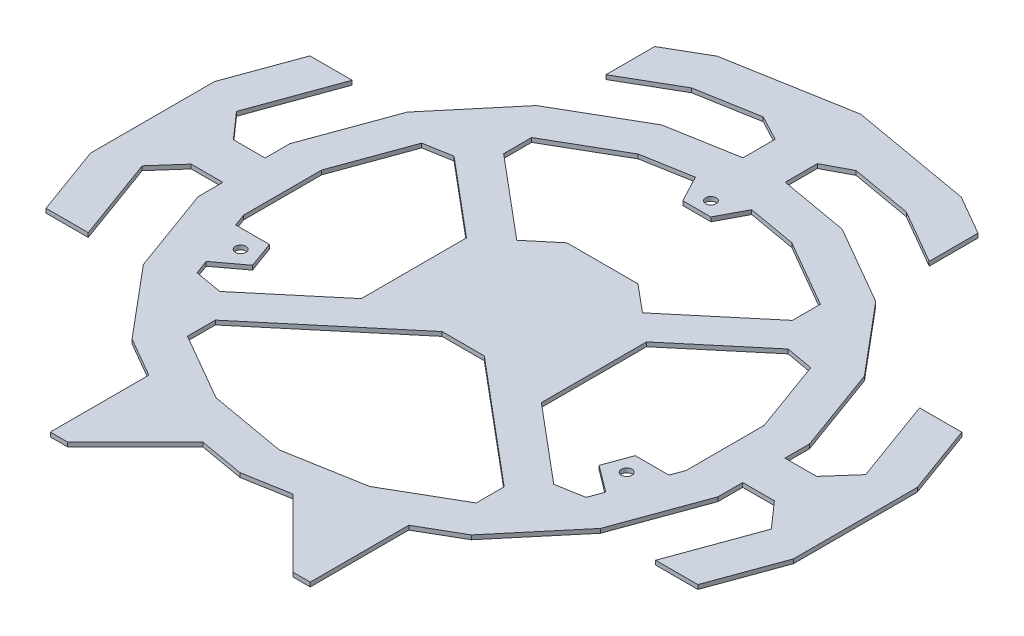
SolidWorks part; units mm, degrees
ref_plane "Front Plane" through (0, 0, 0) normal (0, 0, 1) x (1, 0, 0)
ref_plane "Top Plane" through (0, 0, 0) normal (0, 1, 0) x (1, 0, 0)
ref_plane "Right Plane" through (0, 0, 0) normal (1, 0, 0) x (0, 0, -1)
sketch "Sketch1" plane through (0, 0, 0) normal (0, 1, 0) x (1, 0, 0)
  line L1 (0, 75) -> (-25.6515, 70.4769)
  line L2 (-25.6515, 70.4769) -> (-48.2091, 57.4533)
  line L3 (-48.2091, 57.4533) -> (-64.9519, 37.5)
  line L4 (-64.9519, 37.5) -> (-73.8606, 13.0236)
  line L5 (-73.8606, 13.0236) -> (-73.8606, -13.0236)
  line L6 (-73.8606, -13.0236) -> (-64.9519, -37.5)
  line L7 (-64.9519, -37.5) -> (-48.2091, -57.4533)
  line L8 (-48.2091, -57.4533) -> (-25.6515, -70.4769)
  line L9 (-25.6515, -70.4769) -> (0, -75)
  line L10 (0, -75) -> (25.6515, -70.4769)
  line L11 (25.6515, -70.4769) -> (48.2091, -57.4533)
  line L12 (48.2091, -57.4533) -> (64.9519, -37.5)
  line L13 (64.9519, -37.5) -> (73.8606, -13.0236)
  line L14 (73.8606, -13.0236) -> (73.8606, 13.0236)
  line L15 (73.8606, 13.0236) -> (64.9519, 37.5)
  line L16 (64.9519, 37.5) -> (48.2091, 57.4533)
  line L17 (48.2091, 57.4533) -> (25.6515, 70.4769)
  line L18 (25.6515, 70.4769) -> (0, 75)
  line L19 (0, 63.8303) -> (-21.8313, 59.9809)
  line L20 (-21.8313, 59.9809) -> (-41.0293, 48.8969)
  line L21 (-41.0293, 48.8969) -> (-55.2787, 31.9152)
  line L22 (-55.2787, 31.9152) -> (-62.8606, 11.084)
  line L23 (-62.8606, 11.084) -> (-62.8606, -11.084)
  line L24 (-62.8606, -11.084) -> (-55.2787, -31.9152)
  line L25 (-55.2787, -31.9152) -> (-41.0293, -48.8969)
  line L26 (-41.0293, -48.8969) -> (-21.8313, -59.9809)
  line L27 (-21.8313, -59.9809) -> (0, -63.8303)
  line L28 (0, -63.8303) -> (21.8313, -59.9809)
  line L29 (21.8313, -59.9809) -> (41.0293, -48.8969)
  line L30 (41.0293, -48.8969) -> (55.2787, -31.9152)
  line L31 (55.2787, -31.9152) -> (62.8606, -11.084)
  line L32 (62.8606, -11.084) -> (62.8606, 11.084)
  line L33 (62.8606, 11.084) -> (55.2787, 31.9152)
  line L34 (55.2787, 31.9152) -> (41.0293, 48.8969)
  line L35 (41.0293, 48.8969) -> (21.8313, 59.9809)
  line L36 (21.8313, 59.9809) -> (0, 63.8303)
  circle A0 centre (0, 0) radius 73.8606 construction
  circle A1 centre (0, 0) radius 62.8606 construction
  point P1 (73.8606, 0)
  dimension "D1" = 150
  dimension "D2" = 11
extrude "Boss-Extrude1" add sketch "Sketch1" along normal blind 1.2
sketch "Sketch3" [suppressed] plane through (0, 1.6, 0) normal (0, 1, 0) x (1, 0, 0)
  line L0 (-73.8606, 13.0236) -> (-73.8606, -13.0236) construction
  line L1 (0, 62.8149) -> (-21.484, 59.0267)
  line L2 (-21.484, 59.0267) -> (-40.3766, 48.119)
  line L3 (-40.3766, 48.119) -> (-54.3993, 31.4074)
  line L4 (-54.3993, 31.4074) -> (-61.8606, 10.9077)
  line L5 (-61.8606, 10.9077) -> (-61.8606, -10.9077)
  line L6 (-61.8606, -10.9077) -> (-54.3993, -31.4074)
  line L7 (-54.3993, -31.4074) -> (-40.3766, -48.119)
  line L8 (-40.3766, -48.119) -> (-21.484, -59.0267)
  line L9 (-21.484, -59.0267) -> (0, -62.8149)
  line L10 (0, -62.8149) -> (21.484, -59.0267)
  line L11 (21.484, -59.0267) -> (40.3766, -48.119)
  line L12 (40.3766, -48.119) -> (54.3993, -31.4074)
  line L13 (54.3993, -31.4074) -> (61.8606, -10.9077)
  line L14 (61.8606, -10.9077) -> (61.8606, 10.9077)
  line L15 (61.8606, 10.9077) -> (54.3993, 31.4074)
  line L16 (54.3993, 31.4074) -> (40.3766, 48.119)
  line L17 (40.3766, 48.119) -> (21.484, 59.0267)
  line L18 (21.484, 59.0267) -> (0, 62.8149)
  line L19 (0, -98.3548) -> (33.6393, -92.4233)
  line L20 (33.6393, -92.4233) -> (63.2213, -75.3442)
  line L21 (63.2213, -75.3442) -> (85.1778, -49.1774)
  line L22 (85.1778, -49.1774) -> (96.8606, -17.0791)
  line L23 (96.8606, -17.0791) -> (96.8606, 17.0791)
  line L24 (96.8606, 17.0791) -> (85.1778, 49.1774)
  line L25 (85.1778, 49.1774) -> (63.2213, 75.3442)
  line L26 (63.2213, 75.3442) -> (33.6393, 92.4233)
  line L27 (33.6393, 92.4233) -> (0, 98.3548)
  line L28 (0, 98.3548) -> (-33.6393, 92.4233)
  line L29 (-33.6393, 92.4233) -> (-63.2213, 75.3442)
  line L30 (-63.2213, 75.3442) -> (-85.1778, 49.1774)
  line L31 (-85.1778, 49.1774) -> (-96.8606, 17.0791)
  line L32 (-96.8606, 17.0791) -> (-96.8606, -17.0791)
  line L33 (-96.8606, -17.0791) -> (-85.1778, -49.1774)
  line L34 (-85.1778, -49.1774) -> (-63.2213, -75.3442)
  line L35 (-63.2213, -75.3442) -> (-33.6393, -92.4233)
  line L36 (-33.6393, -92.4233) -> (0, -98.3548)
  circle A0 centre (0, 0) radius 61.8606 construction
  circle A1 centre (0, 0) radius 96.8606 construction
  dimension "D1" = 23
  dimension "D2" = 21.8154
sketch "Sketch15" plane through (0, 0, 0) normal (0, -1, 0) x (1, 0, 0)
  line L1 (0, -101.4011) -> (34.6812, -95.2859)
  line L2 (34.6812, -95.2859) -> (36.9303, -93.9874)
  line L4 (92.6205, -37.5) -> (99.8606, -17.6081)
  line L5 (99.8606, -17.6081) -> (99.8606, 17.6081)
  line L6 (99.8606, 17.6081) -> (92.6205, 37.5)
  line L13 (-92.6205, 37.5) -> (-99.8606, 17.6081)
  line L14 (-99.8606, 17.6081) -> (-99.8606, -17.6081)
  line L15 (-99.8606, -17.6081) -> (-92.6205, -37.5)
  line L17 (-36.9303, -93.9874) -> (-34.6812, -95.2859)
  line L18 (-34.6812, -95.2859) -> (0, -101.4011)
  line L19 (-36.9303, -84.7497) -> (-36.9303, -93.9874)
  line L20 (0, -93.2777) -> (31.9028, -87.6523)
  line L21 (31.9028, -87.6523) -> (36.9303, -84.7497)
  line L23 (84.1071, -37.5) -> (91.8606, -16.1975)
  line L24 (91.8606, -16.1975) -> (91.8606, 16.1975)
  line L25 (91.8606, 16.1975) -> (84.1071, 37.5)
  line L32 (-84.1071, 37.5) -> (-91.8606, 16.1975)
  line L33 (-91.8606, 16.1975) -> (-91.8606, -16.1975)
  line L34 (-91.8606, -16.1975) -> (-84.1071, -37.5)
  line L36 (-36.9303, -84.7497) -> (-31.9028, -87.6523)
  line L37 (-31.9028, -87.6523) -> (0, -93.2777)
  line L38 (-73.8606, -13.0236) -> (-73.8606, 13.0236) construction
  line L39 (84.1071, -37.5) -> (92.6205, -37.5)
  line L40 (-84.1071, -37.5) -> (-92.6205, -37.5)
  line L41 (-84.1071, 37.5) -> (-92.6205, 37.5)
  line L42 (84.1071, 37.5) -> (92.6205, 37.5)
  line L43 (36.9303, -84.7497) -> (36.9303, -93.9874)
  line L46 (76.4976, -64.1891) -> (87.8159, -50.7005) [skipped]
  line L47 (70.3693, -59.0468) -> (80.7808, -46.6388) [skipped]
  line L48 (70.3693, 59.0468) -> (59.9577, 71.4548) [skipped]
  line L49 (87.8159, 50.7005) -> (65.1794, 77.6777) [skipped]
  line L50 (-65.1794, 77.6777) -> (-76.4976, 64.1891) [skipped]
  line L51 (-59.9577, 71.4548) -> (-70.3693, 59.0468) [skipped]
  line L52 (-76.4976, -64.1891) -> (-65.1794, -77.6777) [skipped]
  line L53 (-70.3693, -59.0468) -> (-59.9577, -71.4548) [skipped]
  line L54 (-34.6812, 95.2859) -> (-49.9303, 86.4818) [skipped]
  line L55 (-31.9028, 87.6523) -> (-45.9303, 79.5536) [skipped]
  line L56 (0, 101.4011) -> (-17.3406, 98.3435) [skipped]
  line L57 (0, 93.2777) -> (-15.9514, 90.465) [skipped]
  line L58 (31.9028, 87.6523) -> (0, 93.2777) [skipped]
  line L59 (34.6812, 95.2859) -> (0, 101.4011) [skipped]
  line L60 (49.9303, 86.4818) -> (34.6812, 95.2859) [skipped]
  line L61 (45.9303, 79.5536) -> (31.9028, 87.6523) [skipped]
  arc A0 (92.5521, -37.5) -> (92.5521, 37.5) centre (0, 0) ccw construction
  arc A1 (83.8577, -37.5) -> (83.8577, 37.5) centre (0, 0) ccw construction
  arc A4 (-83.8577, 37.5) -> (-83.8577, -37.5) centre (0, 0) ccw construction
  arc A5 (-92.5521, 37.5) -> (-92.5521, -37.5) centre (0, 0) ccw construction
  arc A6 (-36.9303, -84.1102) -> (36.9303, -84.1102) centre (0, 0) ccw construction
  arc A7 (-36.9303, -92.7809) -> (36.9303, -92.7809) centre (0, 0) ccw construction
  dimension "D4" = 157.7183
  dimension "D1" = 99.8606
  dimension "D3" = 36.9303
  dimension "D2" = 8
extrude "Boss-Extrude17" add sketch "Sketch15" against normal up to surface (1.2 mm away) separate body up to face at (0, 1.2, 0)
sketch "Sketch18" plane through (0, 0, 0) normal (0, -1, 0) x (1, 0, 0)
  line L0 (-91.8606, 6) -> (-73.8606, 6)
  line L1 (-91.8606, -16.1975) -> (-91.8606, 16.1975) construction
  line L2 (-73.8606, -13.0236) -> (-73.8606, 13.0236) construction
  line L3 (-91.8606, -6) -> (-73.8606, -6)
  line L4 (73.8606, 6) -> (91.8606, 6)
  line L5 (73.8606, 13.0236) -> (73.8606, -13.0236) construction
  line L6 (91.8606, 16.1975) -> (91.8606, -16.1975) construction
  line L7 (73.8606, -6) -> (91.8606, -6)
  line L8 (-91.8606, 6) -> (-91.8606, -6)
  line L9 (-73.8606, -6) -> (-73.8606, 6)
  line L10 (73.8606, 6) -> (73.8606, -6)
  line L11 (91.8606, -6) -> (91.8606, 6)
  line L12 (-6, -73.942) -> (-6, -92.2197)
  line L13 (0, -75) -> (-25.6515, -70.4769) construction
  line L14 (0, -93.2777) -> (-31.9028, -87.6523) construction
  line L15 (6, -73.942) -> (6, -92.2197)
  line L16 (25.6515, -70.4769) -> (0, -75) construction
  line L17 (31.9028, -87.6523) -> (0, -93.2777) construction
  line L18 (-6, -73.942) -> (0, -75)
  line L19 (0, -75) -> (6, -73.942)
  line L20 (6, -92.2197) -> (0, -93.2777)
  line L21 (0, -93.2777) -> (-6, -92.2197)
  point P8 (-91.8606, 0)
  dimension "D1" = 12
  dimension "D2" = 6
  dimension "D3" = 12
  dimension "D4" = 6
extrude "Boss-Extrude18" add sketch "Sketch18" against normal up to surface (1.2 mm away) up to face at (0, 1.2, 0)
sketch "Sketch19" plane through (0, 0, 0) normal (0, -1, 0) x (1, 0, 0)
  line L0 (-91.8606, 16.1975) -> (-82.8606, 6)
  line L2 (-73.8606, 6) -> (-91.8606, 6) construction
  line L3 (-91.8606, -16.1975) -> (-82.8606, -6)
  line L4 (-91.8606, -6) -> (-73.8606, -6) construction
  line L5 (-82.8606, -6) -> (-91.8606, -6)
  line L6 (-91.8606, -6) -> (-91.8606, -16.1975)
  line L7 (-82.8606, 6) -> (-91.8606, 6)
  line L8 (-91.8606, 6) -> (-91.8606, 16.1975)
  line L9 (91.8606, 16.1975) -> (82.8606, 6)
  line L10 (91.8606, 6) -> (73.8606, 6) construction
  line L11 (82.8606, 6) -> (91.8606, 6)
  line L12 (91.8606, 6) -> (91.8606, 16.1975)
  line L13 (91.8606, -16.1975) -> (82.8606, -6)
  line L14 (73.8606, -6) -> (91.8606, -6) construction
  line L15 (82.8606, -6) -> (91.8606, -6)
  line L16 (91.8606, -6) -> (91.8606, -16.1975)
  line L17 (18.9514, -89.936) -> (6, -83.0809)
  line L18 (31.9028, -87.6523) -> (6, -92.2197) construction
  line L19 (6, -92.2197) -> (6, -73.942) construction
  line L20 (6, -83.0809) -> (6, -92.2197)
  line L21 (6, -92.2197) -> (18.9514, -89.936)
  line L22 (-6, -83.0809) -> (-6, -92.2197)
  line L23 (-6, -73.942) -> (-6, -92.2197) construction
  line L24 (-6, -92.2197) -> (-18.9514, -89.936)
  line L25 (-6, -92.2197) -> (-31.9028, -87.6523) construction
  line L26 (-18.9514, -89.936) -> (-6, -83.0809)
extrude "Boss-Extrude19" add sketch "Sketch19" against normal up to surface (1.2 mm away) up to face at (0, 1.2, -20.0384)
sketch "Sketch20" plane through (0, 0, 0) normal (0, -1, 0) x (1, 0, 0)
  line L0 (-36.9303, 63.9651) -> (-36.9303, 91.9651)
  line L1 (-48.2091, 57.4533) -> (-25.6515, 70.4769) construction
  line L2 (-36.9303, 91.9651) -> (-32.0524, 91.9651)
  line L3 (-32.0524, 91.9651) -> (-12.8258, 72.7385)
  line L4 (-25.6515, 70.4769) -> (0, 75) construction
  line L6 (25.6515, 70.4769) -> (48.2091, 57.4533) construction
  line L7 (36.9303, 63.9651) -> (36.9303, 91.9651)
  line L8 (36.9303, 91.9651) -> (32.0524, 91.9651)
  line L9 (32.0524, 91.9651) -> (12.8258, 72.7385)
  line L10 (0, 75) -> (25.6515, 70.4769) construction
  line L11 (12.8258, 72.7385) -> (25.6515, 70.4769)
  line L12 (25.6515, 70.4769) -> (36.9303, 63.9651)
  line L13 (-12.8258, 72.7385) -> (-25.6515, 70.4769)
  line L14 (-25.6515, 70.4769) -> (-36.9303, 63.9651)
  dimension "D1" = 135
  dimension "D2" = 135
  dimension "D3" = 28
  dimension "D4" = 28
extrude "Boss-Extrude20" add sketch "Sketch20" against normal up to surface (1.2 mm away) up to face at (0, 1.2, -22.2084)
sketch "Sketch23" plane through (0, 1.2, 0) normal (0, 1, 0) x (1, 0, 0)
  line L0 (-92.6205, 37.5) -> (-80.6205, 37.5)
  line L1 (-80.6205, 37.5) -> (-89.392, 13.4005)
  line L2 (-91.8606, 16.1975) -> (-82.8606, 6) construction
  line L3 (-92.6205, -37.5) -> (-80.6205, -37.5)
  line L4 (-80.6205, -37.5) -> (-89.392, -13.4005)
  line L5 (-82.8606, -6) -> (-91.8606, -16.1975) construction
  line L8 (-99.8606, 17.6081) -> (-92.6205, 37.5) construction
  line L9 (-92.6205, -37.5) -> (-99.8606, -17.6081) construction
  line L10 (-92.6205, 37.5) -> (-99.8606, 17.6081)
  line L11 (-99.8606, 17.6081) -> (-99.8606, -17.6081)
  line L12 (-99.8606, -17.6081) -> (-92.6205, -37.5)
  line L13 (-89.392, -13.4005) -> (-89.392, 13.4005)
  line L14 (0, 63.8303) -> (0, -63.8303) construction
  line L15 (80.6205, -37.5) -> (89.392, -13.4005)
  line L16 (92.6205, -37.5) -> (80.6205, -37.5)
  line L17 (99.8606, -17.6081) -> (92.6205, -37.5)
  line L18 (99.8606, 17.6081) -> (99.8606, -17.6081)
  line L19 (92.6205, 37.5) -> (99.8606, 17.6081)
  line L20 (92.6205, 37.5) -> (80.6205, 37.5)
  line L21 (80.6205, 37.5) -> (89.392, 13.4005)
  line L22 (89.392, -13.4005) -> (89.392, 13.4005)
  dimension "D1" = 12
  dimension "D2" = 12
extrude "Boss-Extrude21" add sketch "Sketch23" against normal up to surface (1.2 mm away) up to face at (0, 0, -11.9896)
sketch "Sketch24" plane through (0, 1.2, 0) normal (0, 1, 0) x (1, 0, 0)
  line L0 (-36.9303, 93.9874) -> (-36.9303, 80.1309)
  line L1 (-36.9303, 80.1309) -> (-30.5137, 83.8356)
  line L3 (-30.5137, 83.8356) -> (-13.1952, 86.8893)
  line L5 (-6, 83.0809) -> (-18.9514, 89.936) construction
  line L7 (-36.9303, 93.9874) -> (-34.6812, 95.2859) construction
  line L8 (-34.6812, 95.2859) -> (0, 101.4011) construction
  line L9 (-36.9303, 93.9874) -> (-34.6812, 95.2859)
  line L10 (-34.6812, 95.2859) -> (0, 101.4011)
  line L11 (0, 101.4011) -> (34.6812, 95.2859)
  line L12 (34.6812, 95.2859) -> (36.9303, 93.9874)
  line L13 (36.9303, 93.9874) -> (36.9303, 80.1309)
  line L14 (36.9303, 80.1309) -> (30.5137, 83.8356)
  line L16 (30.5137, 83.8356) -> (13.1952, 86.8893)
  line L18 (18.9514, 89.936) -> (6, 83.0809) construction
  line L19 (-13.1952, 86.8893) -> (13.1952, 86.8893)
  dimension "D1" = 12
  dimension "D2" = 12
  dimension "D3" = 12
  dimension "D4" = 12
extrude "Boss-Extrude22" add sketch "Sketch24" against normal up to surface (1.2 mm away) up to face at (0, 0, -11.9896)
sketch "Sketch26" plane through (0, 1.2, 0) normal (0, 1, 0) x (1, 0, 0)
  line L0 (-36.9303, 93.9874) -> (-45.9303, 88.7912)
  line L1 (-45.9303, 88.7912) -> (-45.9303, 74.9348)
  line L2 (-45.9303, 74.9348) -> (-36.9303, 80.1309)
  line L3 (36.9303, 93.9874) -> (45.9303, 88.7912)
  line L4 (45.9303, 88.7912) -> (45.9303, 74.9348)
  line L5 (45.9303, 74.9348) -> (36.9303, 80.1309)
  line L6 (30.5137, 83.8356) -> (36.9303, 80.1309) construction
  line L7 (-36.9303, 80.1309) -> (-30.5137, 83.8356) construction
  line L8 (-36.9303, 80.1309) -> (-36.9303, 93.9874) construction
  line L9 (36.9303, 93.9874) -> (36.9303, 80.1309) construction
  line L10 (36.9303, 80.1309) -> (36.9303, 93.9874)
  line L11 (-36.9303, 80.1309) -> (-36.9303, 93.9874)
  dimension "D1" = 9
  dimension "D2" = 9
extrude "Boss-Extrude23" add sketch "Sketch26" against normal up to surface (1.2 mm away) up to face at (0, 0, -11.6192)
sketch "Sketch27" plane through (0, 0, 0) normal (0, -1, 0) x (1, 0, 0)
  line L0 (-44.9401, 44.2362) -> (0, 6.527)
  line L1 (-55.2787, 31.9152) -> (-41.0293, 48.8969) construction
  line L2 (55.2787, -31.9152) -> (41.0293, -48.8969) construction
  line L3 (44.9401, -44.2362) -> (0, -6.527)
  line L4 (44.9401, 44.2362) -> (0, 6.527)
  line L5 (41.0293, 48.8969) -> (55.2787, 31.9152) construction
  line L6 (-41.0293, -48.8969) -> (-55.2787, -31.9152) construction
  line L7 (-44.9401, -44.2362) -> (0, -6.527)
  line L8 (-44.9401, 44.2362) -> (-51.3679, 36.5758)
  line L9 (-51.3679, -36.5758) -> (-44.9401, -44.2362)
  line L10 (44.9401, -44.2362) -> (51.3679, -36.5758)
  line L11 (51.3679, 36.5758) -> (44.9401, 44.2362)
  line L12 (7.7786, 0) -> (51.3679, -36.5758)
  line L13 (-7.7786, 0) -> (-51.3679, 36.5758)
  line L14 (7.7786, 0) -> (51.3679, 36.5758)
  line L15 (-7.7786, 0) -> (-51.3679, -36.5758)
  dimension "D1" = 10
extrude "Boss-Extrude26" add sketch "Sketch27" against normal up to surface (1.2 mm away) up to face at (0, 1.2, -11.284)
sketch "Sketch31" plane through (0, 0, 0) normal (0, -1, 0) x (1, 0, 0)
  line L85 (-10.0984, -28) -> (10.0984, -28)
  line L88 (25.5905, -15.0541) -> (25.5905, 14.9459)
  line L89 (7.7786, 0) -> (51.3679, 36.5758) construction
  line L91 (-51.3679, 36.5758) -> (-7.7786, 0) construction
  line L92 (-25.5905, 14.9459) -> (-25.5905, -15.0541)
  line L93 (-6, 11.5616) -> (6, 11.5616)
  line L94 (0, 6.527) -> (-44.9401, 44.2362) construction
  line L95 (44.9401, 44.2362) -> (0, 6.527) construction
  line L96 (-25.5905, 14.9459) -> (-6, 11.5616)
  line L97 (6, 11.5616) -> (25.5905, 14.9459)
  line L98 (-10.0984, -28) -> (-25.5905, -15.0541)
  line L99 (10.0984, -28) -> (25.5905, -15.0541)
  dimension "D1" = 28
  dimension "D2" = 12
  dimension "D3" = 30
  dimension "D4" = 30
  dimension "D5" = 25.5905
  dimension "D6" = 100.232
extrude "Boss-Extrude29" add sketch "Sketch31" against normal up to surface (1.2 mm away) up to face at (0, 1.2, -47.0732)
sketch "Sketch32" plane through (0, 1.2, 0) normal (0, 1, 0) x (1, 0, 0)
  line L0 (-41.0293, 48.8969) -> (-41.0293, 40.9547)
  line L1 (-44.9401, 44.2362) -> (-17.8604, 21.5137) construction
  line L2 (-41.0293, 40.9547) -> (-44.9401, 44.2362)
  line L3 (-44.9401, 44.2362) -> (-41.0293, 48.8969)
  line L4 (41.0293, 48.8969) -> (41.0293, 40.9547)
  line L5 (17.8604, 21.5137) -> (44.9401, 44.2362) construction
  line L6 (41.0293, 40.9547) -> (44.9401, 44.2362)
  line L7 (44.9401, 44.2362) -> (41.0293, 48.8969)
  line L8 (44.9401, -44.2362) -> (41.0293, -48.8969)
  line L9 (41.0293, -48.8969) -> (41.0293, -40.9547)
  line L10 (44.9401, -44.2362) -> (6, -11.5616) construction
  line L11 (41.0293, -40.9547) -> (44.9401, -44.2362)
  line L12 (-41.0293, -48.8969) -> (-41.0293, -40.9547)
  line L13 (-6, -11.5616) -> (-44.9401, -44.2362) construction
  line L14 (-41.0293, -40.9547) -> (-44.9401, -44.2362)
  line L15 (-44.9401, -44.2362) -> (-41.0293, -48.8969)
extrude "Boss-Extrude30" add sketch "Sketch32" against normal up to surface (1.2 mm away) up to face at (-48.7744, 0, 0)
sketch "Sketch34" plane through (0, 1.2, 0) normal (0, 1, 0) x (1, 0, 0)
  line L5 (8, 62.4197) -> (4, 54.8303)
  line L6 (0, 0) -> (0, -75) construction
  line L7 (-4, 54.8303) -> (4, 54.8303)
  line L9 (-59.0696, -21.4996) -> (-50.6124, -18.4214) construction
  line L10 (-62.8606, -11.084) -> (-55.2787, -31.9152) construction
  line L15 (-8, 62.4197) -> (0, 63.8303)
  line L16 (0, 63.8303) -> (-21.8313, 59.9809) construction
  line L17 (0, 63.8303) -> (8, 62.4197)
  line L18 (21.8313, 59.9809) -> (0, 63.8303) construction
  line L21 (-4, 54.8303) -> (-8, 62.4197)
  line L26 (-61.5581, -14.6626) -> (-56.7698, -27.8183)
  line L32 (-50.6124, -18.4214) -> (-49.2443, -22.1802)
  line L33 (-49.2443, -22.1802) -> (-56.7698, -27.8183)
  line L34 (-50.6124, -18.4214) -> (-51.9805, -14.6626)
  line L35 (-51.9805, -14.6626) -> (-61.5581, -14.6626)
  line L36 (50.6124, -18.4214) -> (49.2443, -22.1802)
  line L37 (49.2443, -22.1802) -> (56.7698, -27.8183)
  line L38 (61.5581, -14.6626) -> (56.7698, -27.8183)
  line L39 (51.9805, -14.6626) -> (61.5581, -14.6626)
  line L40 (50.6124, -18.4214) -> (51.9805, -14.6626)
  dimension "D1" = 8
  dimension "D2" = 14
  dimension "D3" = 4
  dimension "D4" = 9
  dimension "D5" = 16
  dimension "D6" = 8
  dimension "D7" = 4
  dimension "D8" = 9
  dimension "D9" = 8
extrude "Boss-Extrude31" add sketch "Sketch34" against normal up to surface (1.2 mm away) up to face at (0, 0, 42.9576)
sketch "Sketch37" plane through (0, 1.2, 0) normal (0, 1, 0) x (1, 0, 0)
  line L1 (-54.8481, 19.9631) -> (54.8481, 19.9631) construction
  line L2 (-54.8481, 19.9631) -> (-54.8481, -19.9631) construction
  line L3 (-54.8481, -19.9631) -> (54.8481, -19.9631) construction
  line L4 (54.8481, 19.9631) -> (54.8481, -19.9631) construction
  line L5 (-54.8481, 19.9631) -> (54.8481, -19.9631) construction
  line L6 (-54.8481, -19.9631) -> (54.8481, 19.9631) construction
  circle A0 centre (-54.8481, -19.9631) radius 1.5
  circle A1 centre (54.8481, -19.9631) radius 1.5
  point P0 (0, 0)
  dimension "D3" = 3
  dimension "D4" = 3
  dimension "D1" = 109.6963
  dimension "D2" = 39.9262
extrude "Cut-Extrude1" cut sketch "Sketch37" against normal up to surface (1.2 mm away) up to face at (0, 0, -45.228)
sketch "Sketch38" plane through (0, 1.2, 0) normal (0, 1, 0) x (1, 0, 0)
  line L0 (0, 0) -> (0, 58.812) construction
  circle A0 centre (0, 58.812) radius 1.5
  dimension "D2" = 3
  dimension "D1" = 58.812
extrude "Cut-Extrude2" cut sketch "Sketch38" against normal up to surface (1.2 mm away) up to face at (-54.8481, 0, 21.4631)
sketch "Sketch39" plane through (0, 1.2, 0) normal (0, 1, 0) x (1, 0, 0)
  line L1 (-51.3679, 36.5758) -> (-47.4572, 33.2943)
  line L3 (-51.3679, 36.5758) -> (-55.2787, 31.9152)
  line L5 (51.3679, 36.5758) -> (25.5905, 14.9459) construction
  line L7 (55.2787, 31.9152) -> (51.3679, 36.5758) construction
  line L8 (51.3679, 36.5758) -> (55.2787, 31.9152)
  line L10 (51.3679, 36.5758) -> (47.4572, 33.2943)
  line L12 (51.3679, -36.5758) -> (55.2787, -31.9152)
  line L14 (47.4572, -33.2943) -> (51.3679, -36.5758)
  line L15 (-47.4572, -33.2943) -> (-51.3679, -36.5758)
  line L16 (-51.3679, -36.5758) -> (-55.2787, -31.9152)
  line L17 (-41.0293, -40.9547) -> (-47.4572, -33.2943) construction
  line L20 (-55.2787, -31.9152) -> (-47.4572, -33.2943)
  line L22 (-41.0293, 40.9547) -> (-47.4572, 33.2943) construction
  line L23 (-25.5905, 14.9459) -> (-51.3679, 36.5758) construction
  line L24 (41.0293, 40.9547) -> (47.4572, 33.2943) construction
  line L25 (41.0293, -40.9547) -> (47.4572, -33.2943) construction
  line L26 (25.5905, -14.9459) -> (51.3679, -36.5758) construction
  line L27 (47.4572, -33.2943) -> (55.2787, -31.9152)
  line L28 (47.4572, 33.2943) -> (55.2787, 31.9152)
  line L29 (-47.4572, 33.2943) -> (-55.2787, 31.9152)
  dimension "D1" = 10
  dimension "D2" = 10
extrude "Boss-Extrude32" add sketch "Sketch39" against normal up to surface (1.2 mm away) up to face at (0, 0, -57.312)
